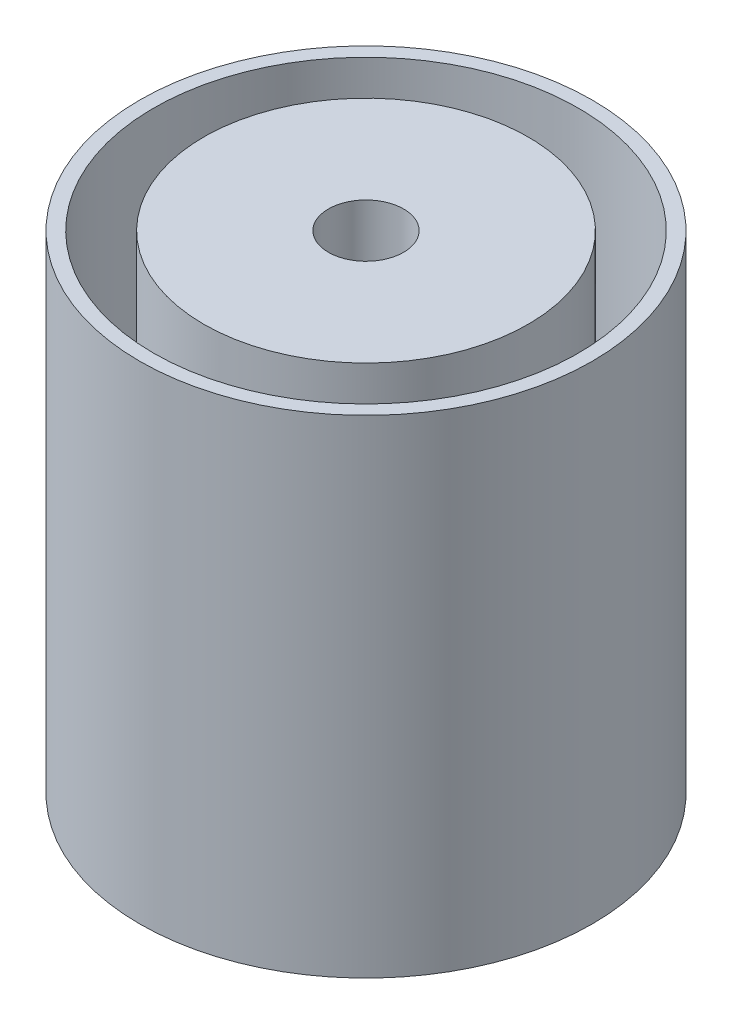
SolidWorks part; units mm, degrees
ref_plane "Front Plane" through (0, 0, 0) normal (0, 0, 1) x (1, 0, 0)
ref_plane "Top Plane" through (0, 0, 0) normal (0, 1, 0) x (1, 0, 0)
ref_plane "Right Plane" through (0, 0, 0) normal (1, 0, 0) x (0, 0, -1)
sketch "Sketch1" plane through (0, 0, 0) normal (0, 1, 0) x (1, 0, 0)
  circle A0 centre (0, 0) radius 16.25
  dimension "D1" = 32.5
extrude "Boss-Extrude1" add sketch "Sketch1" along normal blind 15
sketch "Sketch2" plane through (0, 15, 0) normal (0, 1, 0) x (1, 0, 0)
  circle A0 centre (0, 0) radius 11.65
  dimension "D1" = 23.3
extrude "Boss-Extrude2" add sketch "Sketch2" along normal blind 20
sketch "Sketch3" plane through (0, 15, 0) normal (0, 1, 0) x (1, 0, 0)
  circle A0 centre (0, 0) radius 15.25
  circle A1 centre (0, 0) radius 16.25 construction
  circle A2 centre (0, 0) radius 15.25
  circle M3 centre (0, 0) radius 16.25
  dimension "D1" = 1
  dimension "D2" = 1
extrude "Boss-Extrude4" add sketch "Sketch3" along normal blind 20 contours A0 M3
sketch "Sketch4" plane through (0, 35, 0) normal (0, 1, 0) x (1, 0, 0)
  circle A0 centre (0, 0) radius 2.7
extrude "Cut-Extrude1" cut sketch "Sketch4" against normal blind 30
